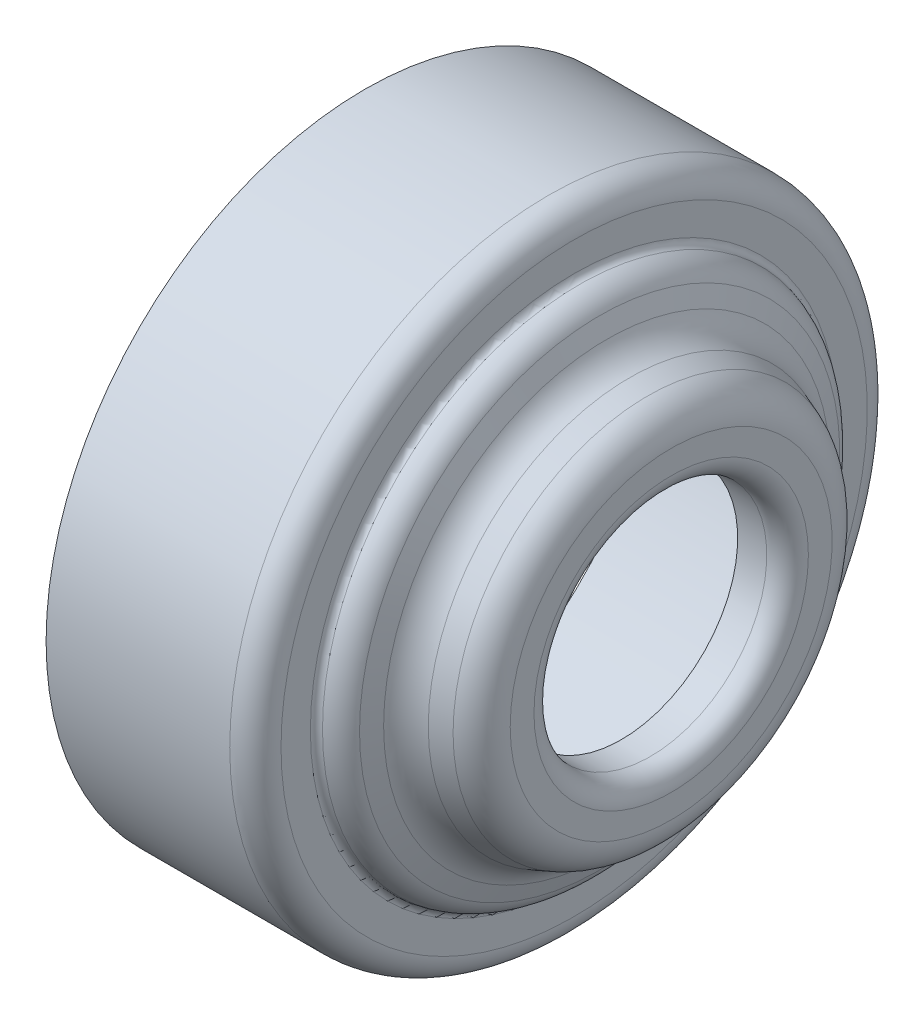
SolidWorks part; units mm, degrees
ref_plane "前视基准面" through (0, 0, 0) normal (0, 0, 1) x (1, 0, 0)
ref_plane "上视基准面" through (0, 0, 0) normal (0, 1, 0) x (1, 0, 0)
ref_plane "右视基准面" through (0, 0, 0) normal (1, 0, 0) x (0, 0, -1)
sketch "草图1" plane through (0, 0, 0) normal (0, 0, 1) x (1, 0, 0)
  line L0 (-28.9725, 0) -> (27.6414, 0) construction
  line L1 (0, 33.7643) -> (0, -38.2898) construction
  line L9 (-14.5, 22) -> (-1.25, 22)
  line L10 (-0.4, 21.15) -> (-0.4, 18.1)
  line L11 (0.1, 17.6) -> (0.5109, 17.6)
  line L12 (1.522, 16.9333) -> (2.0436, 15.7161)
  line L13 (4.2589, 13.6007) -> (5.5618, 13.1121)
  line L14 (6.6, 11.614) -> (6.6, 9.9)
  line L15 (6.1, 9.4) -> (4, 9.4)
  line L17 (4, 9.4) -> (4, 8.4)
  line L18 (-14.5, 23) -> (-1.25, 23)
  line L19 (-0.4, 23.7801) -> (-0.4, -6.5039) construction
  line L20 (0.6, 21.15) -> (0.6, 19.0324)
  line L21 (-14.5, 23) -> (-14.5, 22)
  line L22 (2.4411, 17.3272) -> (2.9628, 16.11)
  line L23 (4.61, 14.537) -> (5.9129, 14.0485)
  line L24 (7.6, 11.614) -> (7.6, 9.9)
  line L25 (6.1, 8.4) -> (4, 8.4)
  line L26 (6.6, 11.614) -> (6.6, 10.5328) construction
  line L27 (0.6, 21.15) -> (0.6, 18.5981) construction
  line L28 (0.6, 18.5981) -> (0.6, 18.5981) construction
  line L29 (4, 9.4) -> (4, 9) construction
  line L30 (5.573, 8.4) -> (4.8, 8.4) construction
  line L31 (5.6477, 9.4) -> (4, 9.4) construction
  line L32 (4.8, 8.4) -> (4.8, 8.4) construction
  line L33 (7.6, 11.614) -> (7.6, 10.6779) construction
  arc A6 (-0.4, 21.15) -> (-1.25, 22) centre (-1.25, 21.15) ccw
  arc A8 (1.522, 16.9333) -> (0.5109, 17.6) centre (0.5109, 16.5) ccw
  arc A9 (2.0436, 15.7161) -> (4.2589, 13.6007) centre (5.6283, 17.2524) ccw
  arc A10 (6.6, 11.614) -> (5.5618, 13.1121) centre (5, 11.614) ccw
  arc A12 (0.1, 17.6) -> (-0.4, 18.1) centre (0.1, 18.1) cw
  arc A13 (0.6, 21.15) -> (-1.25, 23) centre (-1.25, 21.15) ccw
  arc A14 (7.6, 10.6779) -> (5.573, 8.4) centre (5.8037, 10.2356) cw construction
  arc A15 (2.4411, 17.3272) -> (0.9867, 18.5454) centre (0.5109, 16.5) ccw
  arc A16 (2.9628, 16.11) -> (4.61, 14.537) centre (5.6283, 17.2524) ccw
  arc A17 (7.6, 11.614) -> (5.9129, 14.0485) centre (5, 11.614) ccw
  arc A19 (2.4411, 17.3272) -> (0.6, 18.5981) centre (0.5109, 16.5) ccw construction
  arc A20 (0.6, 19.0324) -> (0.9867, 18.5454) centre (1.1, 19.0324) ccw
  arc A21 (0.6, 18.5981) -> (0.6, 18.5981) centre (0.6, 18.5981) cw construction
  arc A22 (6.6, 10.5328) -> (5.6477, 9.4) centre (5.8037, 10.2356) cw construction
  arc A23 (6.6, 9.9) -> (6.1, 9.4) centre (6.1, 9.9) cw
  arc A24 (7.6, 9.9) -> (6.1, 8.4) centre (6.1, 9.9) cw
  point P15 (0, 22.4)
  point P24 (3, 14.5)
  point P27 (7, 13)
  point P30 (7, 9)
  point P54 (0, 0)
  dimension "D11" = 0.85
  dimension "D12" = 0.4
  dimension "D13" = 0.5
  dimension "D14" = 2.6
  dimension "D15" = 1.5
  dimension "D5" = 0.5
  dimension "D8" = 0.5
  dimension "D2" = 18.8
  dimension "D3" = 35.2
  dimension "D4" = 29
  dimension "D6" = 1
  dimension "D7" = 3
  dimension "D9" = 26
  dimension "D10" = 4
  dimension "D18" = 44
revolve "旋转1" add sketch "草图1" angle 360 about L0
